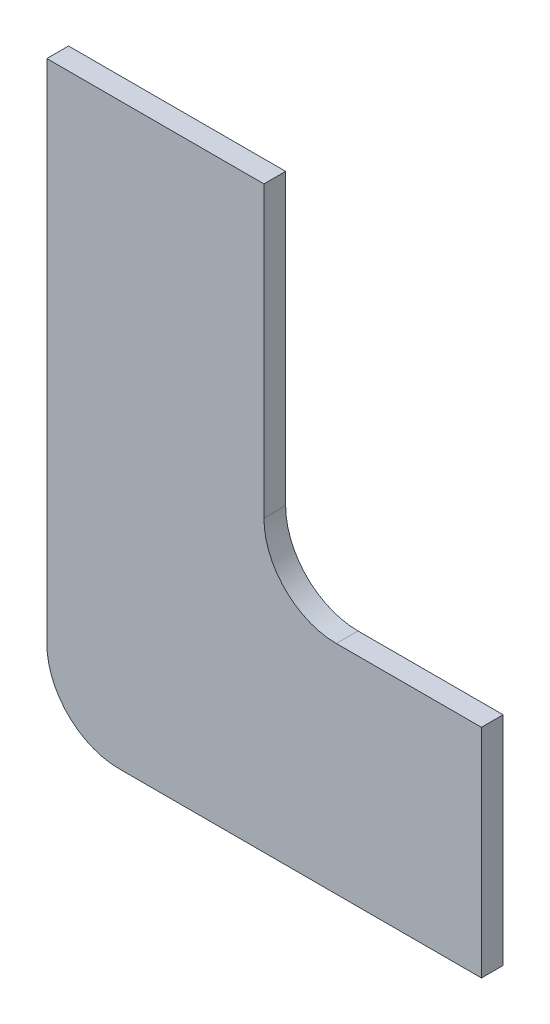
SolidWorks part; units mm, degrees
ref_plane "Front Plane" through (0, 0, 0) normal (0, 0, 1) x (1, 0, 0)
ref_plane "Top Plane" through (0, 0, 0) normal (0, 1, 0) x (1, 0, 0)
ref_plane "Right Plane" through (0, 0, 0) normal (1, 0, 0) x (0, 0, -1)
sketch "Sketch3" plane through (0, 0, 0) normal (0, 0, 1) x (1, 0, 0)
  line L0 (0.15, 0.4) -> (0.15, 0)
  line L1 (-0.15, 0.4) -> (0.15, 0.4)
  line L2 (-0.15, 0.4) -> (-0.15, -0.3)
  line L3 (-0.05, -0.4) -> (0.15, -0.4)
  line L5 (-0.15, 0.4) -> (0.15, -0.4) construction
  line L6 (-0.15, -0.4) -> (0.15, 0.4) construction
  line L7 (0.15, -0.4) -> (0.4506, -0.4)
  line L8 (0.15, -0.4) -> (0.15, -0.1)
  line L9 (0.25, -0.1) -> (0.4506, -0.1)
  line L10 (0.4506, -0.4) -> (0.4506, -0.1)
  arc A0 (0.25, -0.1) -> (0.15, 0) centre (0.25, 0) cw
  arc A1 (-0.05, -0.4) -> (-0.15, -0.3) centre (-0.05, -0.3) cw
  point P0 (0, 0)
  point P26 (0.28, -0.07)
  point P27 (0.28, -0.07)
  dimension "D4" = 0.1
  dimension "D5" = 0.1
  dimension "D1" = 0.3
  dimension "D2" = 0.8
  dimension "D3" = 0.3
extrude "Boss-Extrude2" add sketch "Sketch3" along normal mid plane 0.03 contours L7 L10 L9 A0 L0 L1 L2 A1 L3
